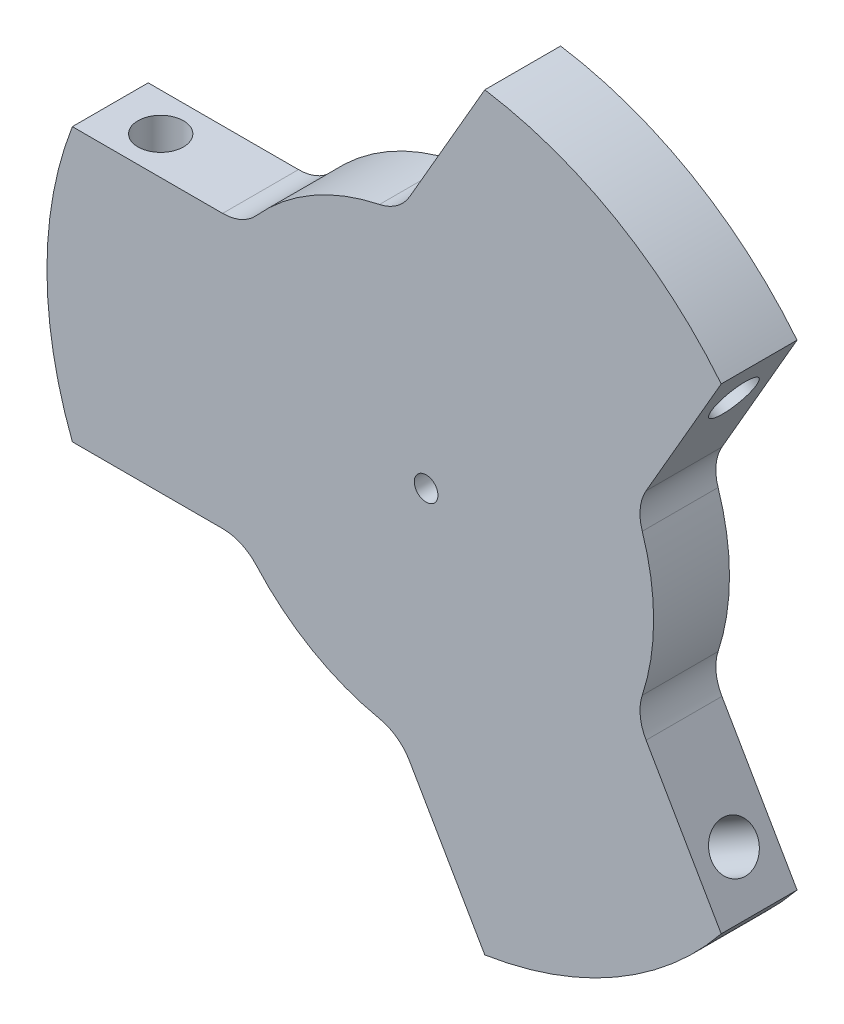
SolidWorks part; units mm, degrees
material "6061 Legierung"
ref_plane "Ebene vorne" through (0, 0, 0) normal (0, 0, 1) x (1, 0, 0)
ref_plane "Ebene oben" through (0, 0, 0) normal (0, 1, 0) x (1, 0, 0)
ref_plane "Ebene rechts" through (0, 0, 0) normal (1, 0, 0) x (0, 0, -1)
sketch "Skizze1" plane through (0, 0, 0) normal (0, 0, 1) x (1, 0, 0)
  circle A0 centre (0, 0) radius 25
  dimension "D1" = 50
extrude "Aufsatz-Linear austragen1" add sketch "Skizze1" along normal blind 5
sketch "Skizze2" plane through (0, 0, 5) normal (0, 0, 1) x (1, 0, 0)
  line L0 (19.4561, 15.699) -> (13.7942, 5.8923)
  line L1 (-23.3238, 9) -> (-12, 9)
  line L2 (-1.7942, 14.8923) -> (3.8677, 24.699)
  line L3 (3.8677, -24.699) -> (-1.7942, -14.8923)
  line L4 (13.7942, -5.8923) -> (19.4561, -15.699)
  line L5 (-12, -9) -> (-23.3238, -9)
  circle A0 centre (0, 0) radius 25 construction
  arc A1 (-1.7942, 14.8923) -> (-12, 9) centre (0, 0) ccw
  arc A2 (13.7942, -5.8923) -> (13.7942, 5.8923) centre (0, 0) ccw
  arc A3 (-12, -9) -> (-1.7942, -14.8923) centre (0, 0) ccw
  arc A4 (3.8677, 24.699) -> (-23.3238, 9) centre (0, 0) ccw
  arc A5 (19.4561, -15.699) -> (19.4561, 15.699) centre (0, 0) ccw
  arc A6 (-23.3238, -9) -> (3.8677, -24.699) centre (0, 0) ccw
  point P18 (0, 0)
  point P29 (-6.224, 0)
  dimension "D3" = 30
  dimension "D1" = 18
  dimension "D2" = 9
  dimension "D4" = 3
extrude "Schnitt-Linear austragen1" cut sketch "Skizze2" against normal through all
sketch "Skizze3" plane through (0, 9, 0) normal (0, 1, 0) x (1, 0, 0)
  line L0 (-23.3238, -5) -> (-12, -5) construction
  circle A0 centre (-20, -2.5) radius 1.5
  dimension "D1" = 3
  dimension "D2" = 2.5
  dimension "D3" = 20
extrude "Schnitt-Linear austragen2" cut sketch "Skizze3" against normal through all
pattern_circular "Kreismuster1" count 3 over 360 about axis through (0, 0, 5) along (0, 0, -1) of "Schnitt-Linear austragen2"
sketch "Skizze6" plane through (0, 0, 5) normal (0, 0, 1) x (1, 0, 0)
  circle A0 centre (0, 0) radius 0.78
  dimension "D1" = 1.56
extrude "Schnitt-Linear austragen5" cut sketch "Skizze6" against normal through all
fillet "Verrundung1" radius 3 6 edges at (13.7942, 5.8923, 2.5) (13.7942, -5.8923, 2.5) (-1.7942, -14.8923, 2.5) (-12, -9, 2.5) (-12, 9, 2.5) (-1.7942, 14.8923, 2.5)
